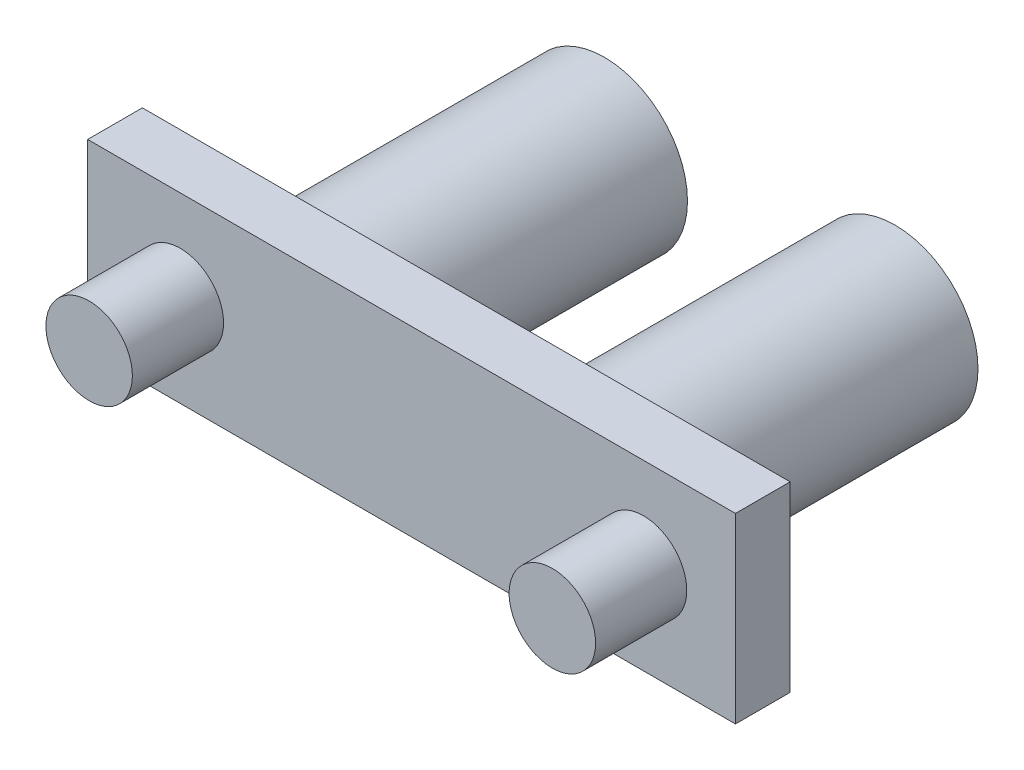
SolidWorks part; units mm, degrees
ref_plane "Front Plane" through (0, 0, 0) normal (0, 0, 1) x (1, 0, 0)
ref_plane "Top Plane" through (0, 0, 0) normal (0, 1, 0) x (1, 0, 0)
ref_plane "Right Plane" through (0, 0, 0) normal (1, 0, 0) x (0, 0, -1)
sketch "Sketch1" plane through (0, 0, 0) normal (0, 0, 1) x (1, 0, 0)
  line L0 (0, 0) -> (17.76, 0)
  line L1 (17.76, 0) -> (17.76, 5)
  line L2 (17.76, 5) -> (0, 5)
  line L3 (0, 5) -> (0, 0)
  dimension "D1" = 17.76
  dimension "D2" = 5
extrude "Boss-Extrude1" add sketch "Sketch1" along normal blind 1.5
sketch "Sketch2" plane through (0, 0, 1.5) normal (0, 0, 1) x (1, 0, 0)
  line L0 (0, 5) -> (0, 0) construction
  line L1 (0, 0) -> (17.76, 0) construction
  circle A0 centre (2.54, 2.5) radius 1.185
  circle A1 centre (15.24, 2.5) radius 1.185
  dimension "D2" = 2.54
  dimension "D3" = 2.37
  dimension "D4" = 2.37
  dimension "D1" = 12.7
  dimension "D5" = 2.5
extrude "Boss-Extrude2" add sketch "Sketch2" along normal blind 2.5
sketch "Sketch3" plane through (0, 0, 0) normal (0, 0, -1) x (-1, 0, 0)
  line L1 (0, 5) -> (0, 0) construction
  line L2 (-17.76, 5) -> (0, 5) construction
  circle A0 centre (-12.875, 2.5) radius 2.275
  circle A1 centre (-4.91, 2.5) radius 2.275
  circle A2 centre (-12.875, 2.5) radius 1.6
  circle A3 centre (-4.91, 2.5) radius 1.6015
  dimension "D2" = 4.91
  dimension "D3" = 4.55
  dimension "D4" = 4.55
  dimension "D5" = 2.5
  dimension "D6" = 2.5
  dimension "D7" = 3.2
  dimension "D8" = 3.203
  dimension "D1" = 7.965
extrude "Boss-Extrude3" add sketch "Sketch3" along normal blind 7.76
